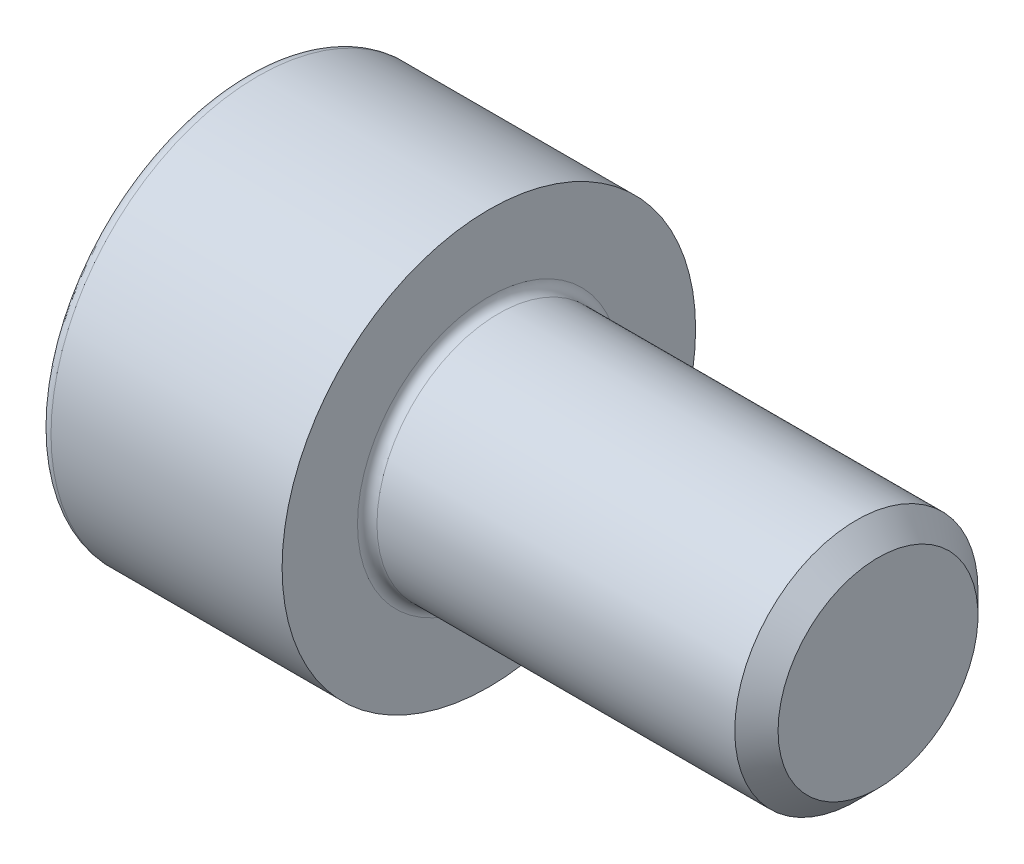
SolidWorks part; units mm, degrees
ref_plane "Front Plane" through (0, 0, 0) normal (0, 0, 1) x (1, 0, 0)
ref_plane "Top Plane" through (0, 0, 0) normal (0, 1, 0) x (1, 0, 0)
ref_plane "Right Plane" through (0, 0, 0) normal (1, 0, 0) x (0, 0, -1)
sketch "BodySke" plane through (0, 0, 0) normal (0, 0, 1) x (1, 0, 0)
  line L0 (0, 0) -> (5.8492, 0) construction
  line L1 (0, 0) -> (0, 4.25)
  line L2 (0, 4.25) -> (5, 4.25)
  line L3 (5, 4.25) -> (5, 2.5)
  line L4 (5, 2.5) -> (12.555, 2.5)
  line L5 (12.555, 2.5) -> (13, 2.055)
  line L6 (13, 2.055) -> (13, 0)
  line L7 (13, 0) -> (0, 0)
  line L8 (5, 0) -> (5, 0.601) construction
  line L9 (5.8, 1.5877) -> (5.8, 0.9267) construction
  dimension "Body_chamfer_angle" = 45
revolve "BaseBody" add sketch "BodySke" angle 360 about L0
cosmetic thread "ThreadCosmetic" [suppressed] parameters "Thread_length"=12, "Thread_minor"=1.548
fillet "Fillet1" radius 0.2 1 edges at (5, 0, 2.5)
fillet "Fillet2" radius 0.25 1 edges at (0, 0, 4.25)
sketch "HexSke" plane through (0, 0, 0) normal (1, 0, 0) x (0, 0, -1)
  line L1 (0, 2.3094) -> (-2, 1.1547)
  line L2 (-2, 1.1547) -> (-2, -1.1547)
  line L3 (-2, -1.1547) -> (0, -2.3094)
  line L4 (0, -2.3094) -> (2, -1.1547)
  line L5 (2, -1.1547) -> (2, 1.1547)
  line L6 (2, 1.1547) -> (0, 2.3094)
  circle A0 centre (0, 0) radius 2 construction
extrude "Hex" cut sketch "HexSke" along normal blind 2.5
sketch "Hex-PreBroachSke" plane through (0, 0, 0) normal (0, 0, 1) x (1, 0, 0)
  line L0 (0, 0) -> (4.7325, 0) construction
  line L1 (0, 4) -> (0, -4) construction
  line L2 (0, 0) -> (0, 2)
  line L3 (0, 2) -> (2.5, 2)
  line L4 (2.5, 2) -> (3.6547, 0)
  line L5 (3.6547, 0) -> (0, 0)
  dimension "Hex_depth" = 1
  dimension "D1" = 1.5
  dimension "Angle" = 60
revolve "Hex-PreBroach" cut sketch "Hex-PreBroachSke" angle 360 about L0
sketch "ThdSchSke" plane through (0, 0, 0) normal (0, 0, 1) x (1, 0, 0)
  line L0 (0, 0) -> (4.4125, 0) construction
  line L1 (0, 4) -> (0, -4) construction
  line L2 (11.755, 3.0138) -> (11.755, 2.5)
  line L3 (11.755, 3.0138) -> (12.2688, 3.0138)
  line L4 (12.2688, 3.0138) -> (12.2688, 2.5)
  line L5 (12.2688, 2.5) -> (12.0119, 2.055)
  line L6 (12.0119, 2.055) -> (11.755, 2.5)
  dimension "D1" = 0.4
revolve "ThreadSchematic" [suppressed] cut sketch "ThdSchSke" angle 360 about L0
pattern_linear "ThdSchPat" [suppressed]
equation "\"Thread_length@ThreadCosmetic\" = \"Thread_length@BodySke\""
equation "\"Thread_minor@ThreadCosmetic\" = \"Thread_minor@BodySke\""
equation "\"Hex_depth@Hex-PreBroachSke\" = \"Hex_length@Hex\""
equation "\"D1@Hex-PreBroachSke\" = \"Hex_size@HexSke\""
equation "\"D1@ThdSchSke\" = \"Advance@BodySke\""
equation "\"Advance@ThdSchPat\" = \"Advance@BodySke\""
equation "\"Tooth_Num@ThdSchPat\" =  int( \"Thread_length@BodySke\" / \"Advance@BodySke\" )  - 1"
